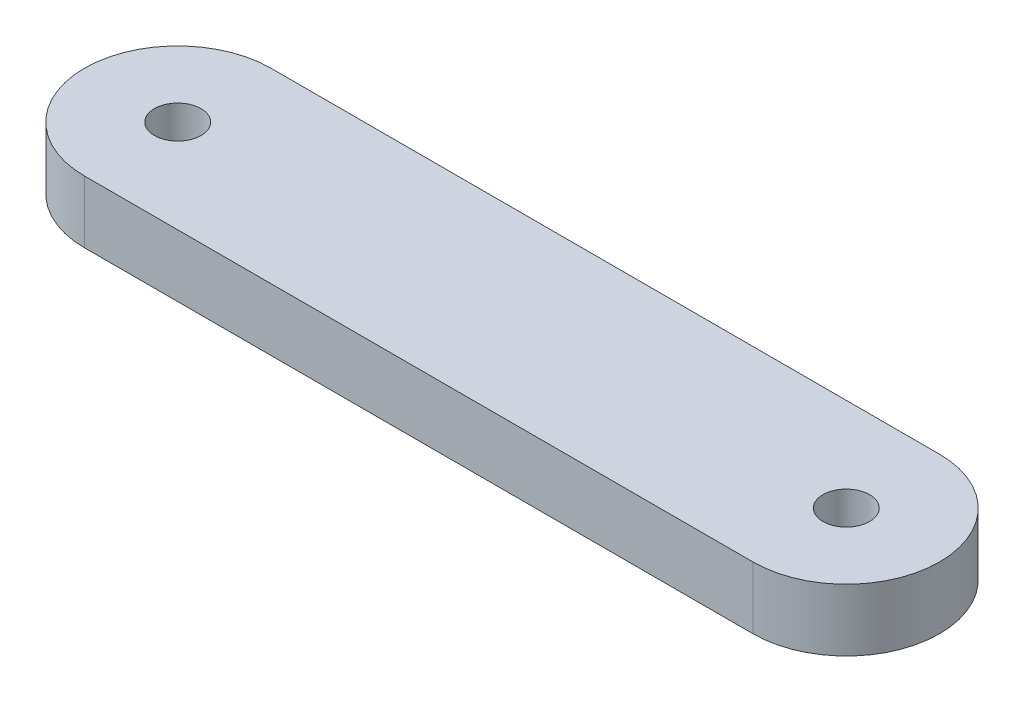
SolidWorks part; units mm, degrees
ref_plane "Front Plane" through (0, 0, 0) normal (0, 0, 1) x (1, 0, 0)
ref_plane "Top Plane" through (0, 0, 0) normal (0, 1, 0) x (1, 0, 0)
ref_plane "Right Plane" through (0, 0, 0) normal (1, 0, 0) x (0, 0, -1)
sketch "Sketch1" plane through (0, 0, 0) normal (0, 1, 0) x (1, 0, 0)
  line L0 (-21.5, 0) -> (21.5, 0) construction
  line L1 (-21.5, 6) -> (21.5, 6)
  line L2 (-21.5, -6) -> (21.5, -6)
  arc A0 (-21.5, 6) -> (-21.5, -6) centre (-21.5, 0) ccw
  arc A1 (21.5, -6) -> (21.5, 6) centre (21.5, 0) ccw
  circle A2 centre (-21.5, 0) radius 1.5
  circle A3 centre (21.5, 0) radius 1.5
  point P3 (0, 0)
  dimension "D1" = 6
  dimension "D3" = 3
  dimension "D2" = 43
extrude "Boss-Extrude1" add sketch "Sketch1" along normal blind 4
